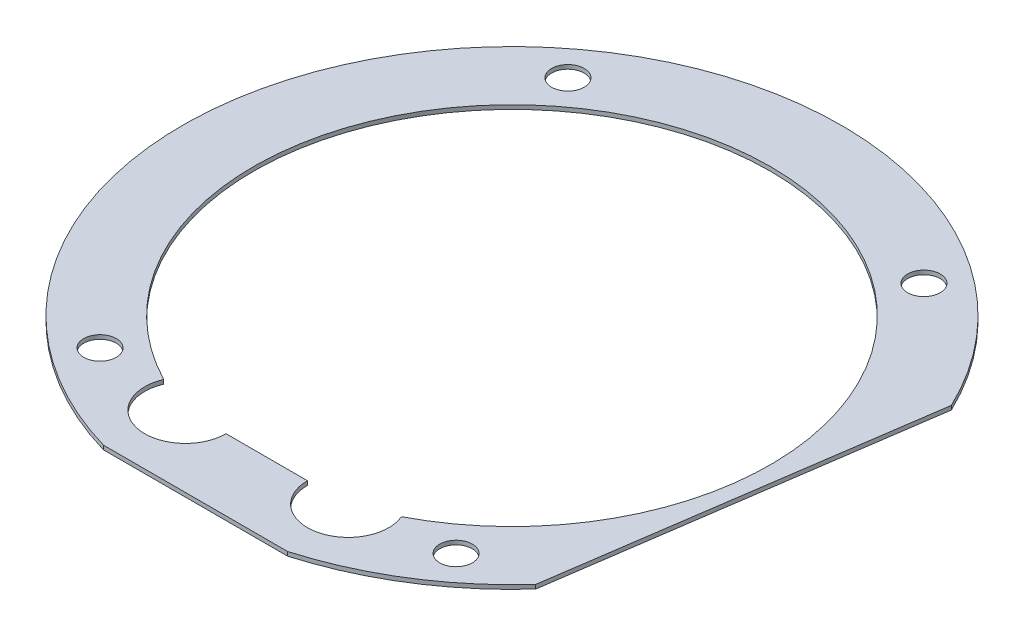
SolidWorks part; units mm, degrees
ref_plane "Front Plane" through (0, 0, 0) normal (0, 0, 1) x (1, 0, 0)
ref_plane "Top Plane" through (0, 0, 0) normal (0, 1, 0) x (1, 0, 0)
ref_plane "Right Plane" through (0, 0, 0) normal (1, 0, 0) x (0, 0, -1)
sketch "Sketch1" plane through (0, 0, 0) normal (0, 1, 0) x (1, 0, 0)
  line L1 (-4, -24.1073) -> (4, -24.1073)
  line L2 (29.2378, 13.961) -> (24.0491, -21.7118)
  line L3 (-9.0608, -31.1073) -> (9.0608, -31.1073)
  arc A0 (11.6854, -22.5524) -> (-11.6854, -22.5524) centre (0, 0) ccw
  circle A1 centre (-17.5, 23) radius 1.6
  arc A2 (9.0608, -31.1073) -> (24.0491, -21.7118) centre (0, 0) ccw
  arc A3 (29.2378, 13.961) -> (-9.0608, -31.1073) centre (0, 0) ccw
  circle A4 centre (-17.5, -23) radius 1.6
  circle A5 centre (17.5, -23) radius 1.6
  circle A6 centre (17.5, 23) radius 1.6
  arc A7 (-4, -24.1073) -> (-11.6854, -22.5524) centre (-8, -24.1073) cw
  arc A8 (4, -24.1073) -> (11.6854, -22.5524) centre (8, -24.1073) ccw
  dimension "D1" = 3.2
  dimension "D2" = 3.2
  dimension "D3" = 3.2
  dimension "D4" = 3.2
  dimension "D10" = 7
  dimension "D11" = 25.4
  dimension "D12" = 32.4
  dimension "D15" = 4
  dimension "D16" = 4
  dimension "D5" = 17.5
  dimension "D6" = 23
  dimension "D7" = 46
  dimension "D8" = 35
  dimension "D9" = 7
  dimension "D13" = 16
  dimension "D14" = 36.0481
  dimension "D17" = 8
  dimension "D18" = 7.8411
  dimension "D19" = 7.8411
extrude "Boss-Extrude1" add sketch "Sketch1" along normal blind 0.4
